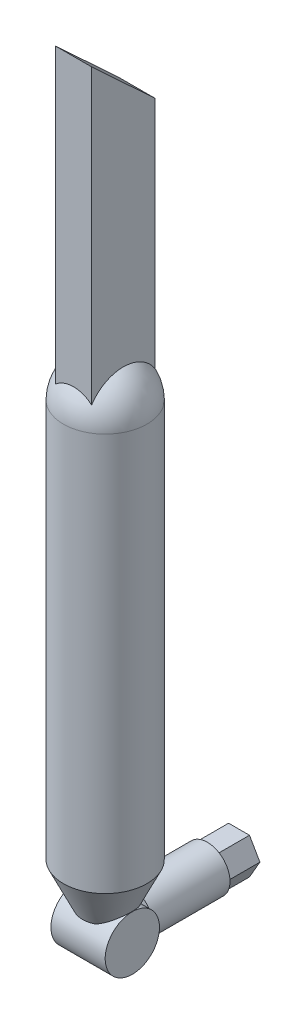
SolidWorks part; units mm, degrees
material "ABS"
ref_plane "Front Plane" through (0, 0, 0) normal (0, 0, 1) x (1, 0, 0)
ref_plane "Top Plane" through (0, 0, 0) normal (0, 1, 0) x (1, 0, 0)
ref_plane "Right Plane" through (0, 0, 0) normal (1, 0, 0) x (0, 0, -1)
sketch "Sketch1" plane through (0, 0, 0) normal (0, 0, 1) x (1, 0, 0)
  line L0 (4.6188, 0) -> (2.3094, 4)
  line L1 (2.3094, 4) -> (-2.3094, 4)
  line L2 (-2.3094, 4) -> (-4.6188, 0)
  line L3 (-4.6188, 0) -> (-2.3094, -4)
  line L4 (-2.3094, -4) -> (2.3094, -4)
  line L5 (2.3094, -4) -> (4.6188, 0)
extrude "SMA_Nut" add sketch "Sketch1" along normal blind 7
sketch "Sketch2" plane through (0, 0, 0) normal (0, 0, 1) x (1, 0, 0)
  circle A0 centre (0, 0) radius 3.175
extrude "SMA_Bore" cut sketch "Sketch2" along normal blind 5
ref_plane "Plane1" through (0, 0, 7) normal (0, 0, 1) x (1, 0, 0)
sketch "Sketch3" plane through (0, 0, 7) normal (0, 0, 1) x (1, 0, 0)
  circle A0 centre (0, 0) radius 5
extrude "Sleeve" add sketch "Sketch3" along normal blind 17 separate body
sketch "Sketch4" plane through (0, 0, 0) normal (1, 0, 0) x (0, 0, -1)
  circle A0 centre (-29.6, 0) radius 6
extrude "Swivel_Knuckle" add sketch "Sketch4" along normal mid plane 12
sketch "Sketch5" plane through (0, 0, 0) normal (1, 0, 0) x (0, 0, -1)
  line L0 (-29.6, 2) -> (-29.6, 112.25) construction
  line L1 (-29.6, 4) -> (-34.6, 4)
  line L2 (-34.6, 4) -> (-38.85, 13)
  line L3 (-38.85, 13) -> (-38.85, 101)
  line L4 (-29.6, 110.25) -> (-29.6, 4)
  arc A0 (-38.85, 101) -> (-29.6, 110.25) centre (-29.6, 101) cw
revolve "Radome_Boot" add sketch "Sketch5" angle 360 about L0
sketch "Sketch6" plane through (0, 0, 0) normal (1, 0, 0) x (0, 0, -1)
  line L0 (-22.6, 95) -> (-36.6, 95)
  line L1 (-36.6, 95) -> (-36.6, 170.3)
  line L2 (-36.6, 170.3) -> (-22.6, 157.3)
  line L3 (-22.6, 157.3) -> (-22.6, 95)
extrude "Whip_Blade" add sketch "Sketch6" along normal mid plane 8
